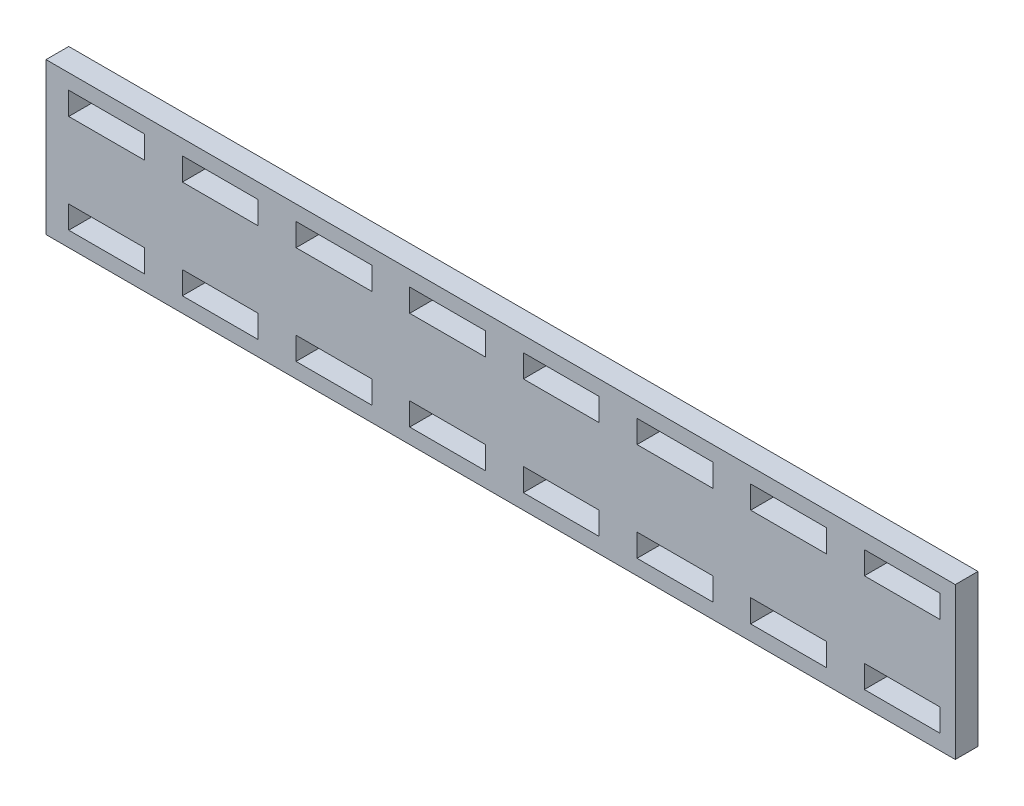
SolidWorks part; units mm, degrees
material "Thornel Mat VMA"
ref_plane "前视基准面" through (0, 0, 0) normal (0, 0, 1) x (1, 0, 0)
ref_plane "上视基准面" through (0, 0, 0) normal (0, 1, 0) x (1, 0, 0)
ref_plane "右视基准面" through (0, 0, 0) normal (1, 0, 0) x (0, 0, -1)
sketch "草图1" plane through (0, 0, 0) normal (0, 0, 1) x (1, 0, 0)
  line L0 (-35, 5) -> (-35, 8)
  line L2 (-53, 5) -> (-53, -5)
  line L4 (67, 5) -> (67, -5)
  line L5 (-50, 5) -> (-40, 5)
  line L6 (-35, 5) -> (-25, 5)
  line L7 (-50, 5) -> (-50, 8)
  line L8 (-50, 8) -> (-40, 8)
  line L9 (-40, 5) -> (-40, 8)
  line L10 (-25, 5) -> (-25, 8)
  line L11 (-35, 8) -> (-25, 8)
  line L12 (-20, 5) -> (-20, 8)
  line L13 (-10, 5) -> (-10, 8)
  line L14 (-20, 8) -> (-10, 8)
  line L15 (-5, 5) -> (-5, 8)
  line L16 (5, 5) -> (5, 8)
  line L17 (-5, 8) -> (5, 8)
  line L18 (10, 5) -> (10, 8)
  line L19 (20, 5) -> (20, 8)
  line L20 (10, 8) -> (20, 8)
  line L21 (25, 5) -> (25, 8)
  line L22 (35, 5) -> (35, 8)
  line L23 (25, 8) -> (35, 8)
  line L24 (40, 5) -> (40, 8)
  line L25 (50, 5) -> (50, 8)
  line L26 (40, 8) -> (50, 8)
  line L27 (50, -5) -> (50, -8)
  line L28 (40, -8) -> (50, -8)
  line L29 (40, -5) -> (40, -8)
  line L30 (35, -5) -> (35, -8)
  line L31 (25, -8) -> (35, -8)
  line L32 (25, -5) -> (25, -8)
  line L33 (20, -5) -> (20, -8)
  line L34 (10, -8) -> (20, -8)
  line L35 (10, -5) -> (10, -8)
  line L36 (5, -5) -> (5, -8)
  line L37 (-5, -8) -> (5, -8)
  line L38 (-5, -5) -> (-5, -8)
  line L39 (-10, -5) -> (-10, -8)
  line L40 (-20, -8) -> (-10, -8)
  line L41 (-20, -5) -> (-20, -8)
  line L42 (-25, -5) -> (-25, -8)
  line L43 (-35, -8) -> (-25, -8)
  line L44 (-35, -5) -> (-35, -8)
  line L45 (-50, -8) -> (-40, -8)
  line L46 (-40, -5) -> (-40, -8)
  line L47 (-50, -5) -> (-50, -8)
  line L62 (-53, 5) -> (-53, 10)
  line L63 (-53, 10) -> (67, 10)
  line L64 (67, 10) -> (67, 5)
  line L65 (55, 0) -> (-55, 0) construction
  line L66 (-53, -10) -> (67, -10)
  line L67 (-53, -5) -> (-53, -10)
  line L68 (67, -10) -> (67, -5)
  line L69 (-20, 5) -> (-10, 5)
  line L70 (-5, 5) -> (5, 5)
  line L71 (10, 5) -> (20, 5)
  line L72 (25, 5) -> (35, 5)
  line L73 (40, 5) -> (50, 5)
  line L74 (-50, -5) -> (-40, -5)
  line L75 (-35, -5) -> (-25, -5)
  line L76 (-20, -5) -> (-10, -5)
  line L77 (-5, -5) -> (5, -5)
  line L78 (10, -5) -> (20, -5)
  line L79 (25, -5) -> (35, -5)
  line L80 (40, -5) -> (50, -5)
  line L81 (55, 5) -> (65, 5)
  line L82 (65, 5) -> (65, 8)
  line L83 (55, 8) -> (65, 8)
  line L84 (55, 5) -> (55, 8)
  line L85 (55, -5) -> (55, -8)
  line L86 (55, -8) -> (65, -8)
  line L87 (65, -5) -> (65, -8)
  line L88 (55, -5) -> (65, -5)
  point P0 (0, 0)
  dimension "D1" = 120
  dimension "D2" = 10
  dimension "D3" = 10
  dimension "D4" = 3
  dimension "D5" = 3
  dimension "D6" = 2
extrude "凸台-拉伸1" add sketch "草图1" along normal blind 3
